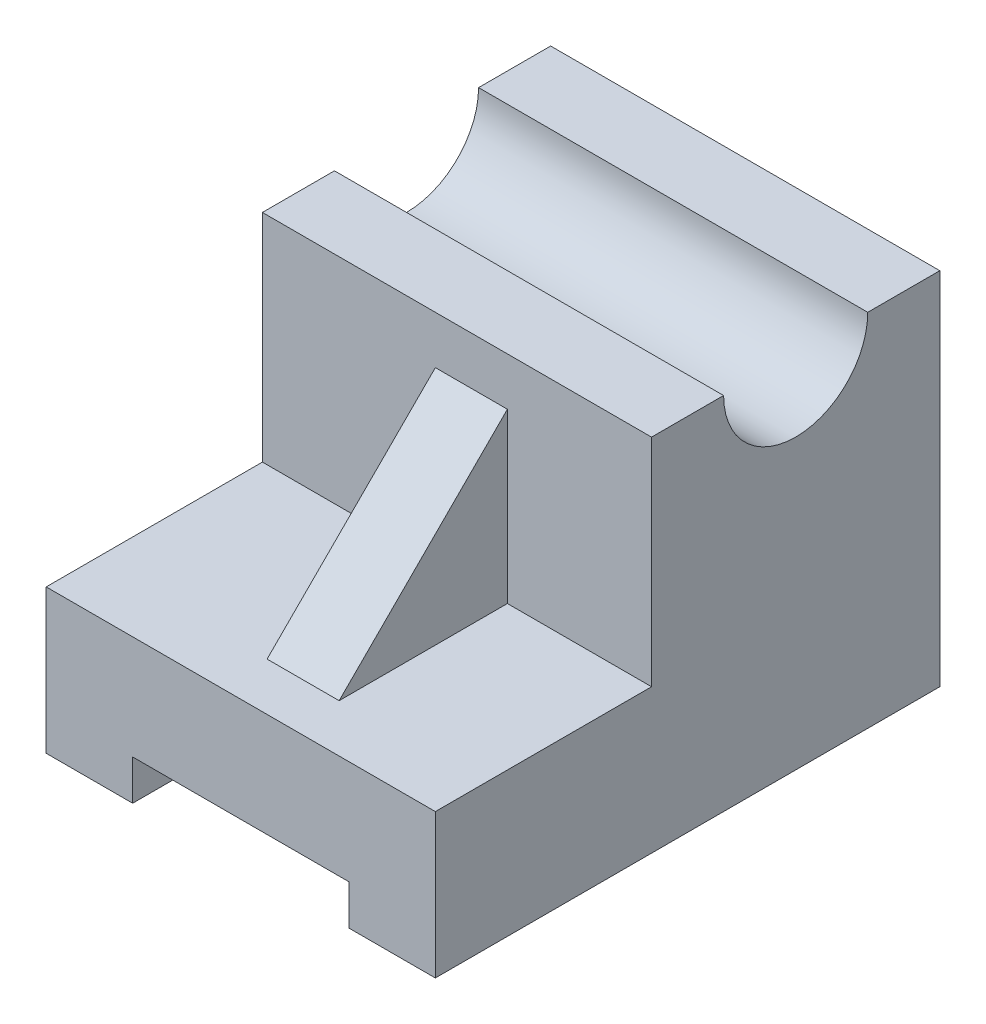
SolidWorks part; units mm, degrees
ref_plane "Front Plane" through (0, 0, 0) normal (0, 0, 1) x (1, 0, 0)
ref_plane "Top Plane" through (0, 0, 0) normal (0, 1, 0) x (1, 0, 0)
ref_plane "Right Plane" through (0, 0, 0) normal (1, 0, 0) x (0, 0, -1)
sketch "Sketch1" plane through (0, 0, 0) normal (1, 0, 0) x (0, 0, -1)
  line L0 (42.0557, 47.9259) -> (2.0557, 47.9259)
  line L1 (2.0557, 47.9259) -> (2.0557, 17.9259)
  line L2 (2.0557, 17.9259) -> (-27.9443, 17.9259)
  line L3 (-27.9443, 17.9259) -> (-27.9443, -2.0741)
  line L4 (-27.9443, -2.0741) -> (42.0557, -2.0741)
  line L5 (42.0557, -2.0741) -> (42.0557, 47.9259)
  dimension "D1" = 70
  dimension "D2" = 50
  dimension "D3" = 40
  dimension "D4" = 30
  dimension "D5" = 20
extrude "Boss-Extrude1" add sketch "Sketch1" along normal blind 54
sketch "Sketch2" plane through (54, 0, 0) normal (1, 0, 0) x (0, 0, -1)
  line L0 (42.0557, 47.9259) -> (2.0557, 47.9259) construction
  circle A0 centre (22.0557, 47.9259) radius 10
  dimension "D1" = 20
  dimension "D2" = 20
extrude "Cut-Extrude1" cut sketch "Sketch2" against normal through all
ref_plane "Plane4" through (34, 0, 0) normal (1, 0, 0) x (0, 0, -1)
sketch "Sketch5" plane through (34, 0, 0) normal (1, 0, 0) x (0, 0, -1)
  line L0 (4.5546, 43.7744) -> (-25.3916, 13.8282)
rib "Rib4" sketch "Sketch5" sketch "Sketch5" thickness 10 extrusion direction parallel to sketch draft on no parameters "D1"=10
sketch "Sketch6" plane through (0, 0, 27.9443) normal (0, 0, 1) x (1, 0, 0)
  line L0 (54, -2.0741) -> (0, -2.0741) construction
  line L1 (42, -7.6399) -> (12, -7.6399)
  line L2 (42, -7.6399) -> (42, 3.4916)
  line L3 (42, 3.4916) -> (12, 3.4916)
  line L4 (12, -7.6399) -> (12, 3.4916)
  line L5 (42, -7.6399) -> (12, 3.4916) construction
  line L6 (42, 3.4916) -> (12, -7.6399) construction
  line L7 (0, 17.9259) -> (0, -2.0741) construction
  line L8 (54, 17.9259) -> (54, -2.0741) construction
  point P0 (27, -2.0741)
  dimension "D1" = 12
  dimension "D2" = 12
extrude "Cut-Extrude2" cut sketch "Sketch6" against normal through all
